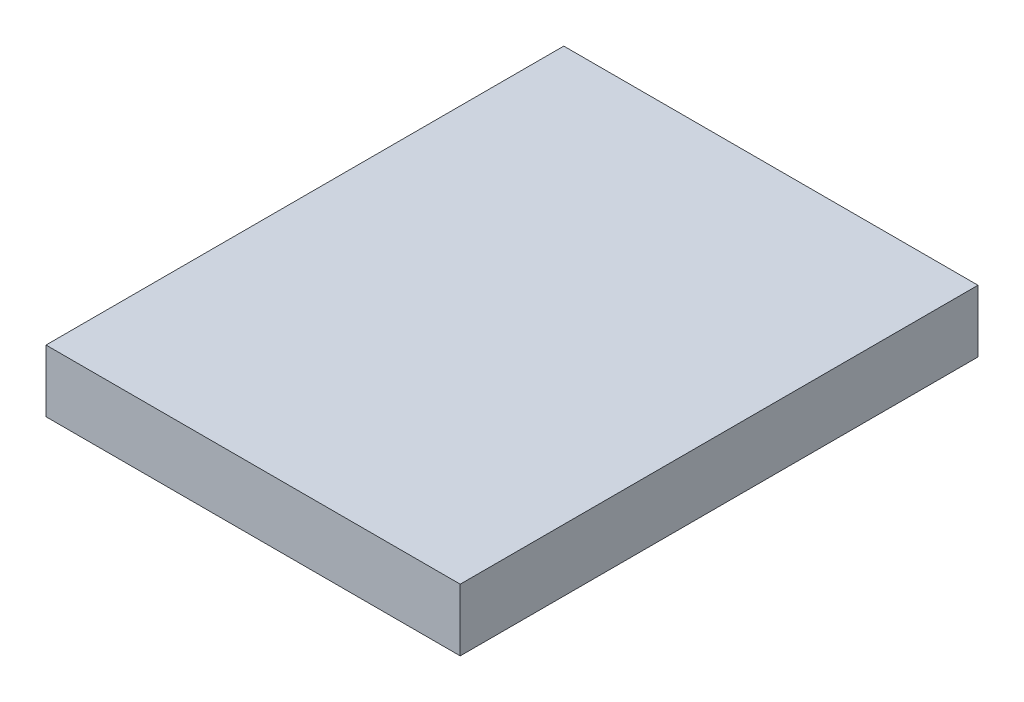
SolidWorks part; units mm, degrees
ref_plane "Front Plane" through (0, 0, 0) normal (0, 0, 1) x (1, 0, 0)
ref_plane "Top Plane" through (0, 0, 0) normal (0, 1, 0) x (1, 0, 0)
ref_plane "Right Plane" through (0, 0, 0) normal (1, 0, 0) x (0, 0, -1)
sketch "Sketch1" plane through (0, 0, 0) normal (0, 1, 0) x (1, 0, 0)
  line L1 (10, -12.5) -> (-10, -12.5)
  line L2 (10, -12.5) -> (10, 12.5)
  line L3 (10, 12.5) -> (-10, 12.5)
  line L4 (-10, -12.5) -> (-10, 12.5)
  line L5 (10, -12.5) -> (-10, 12.5) construction
  line L6 (10, 12.5) -> (-10, -12.5) construction
  point P0 (0, 0)
  dimension "D1" = 25
  dimension "D2" = 20
extrude "Boss-Extrude1" add sketch "Sketch1" along normal blind 3
